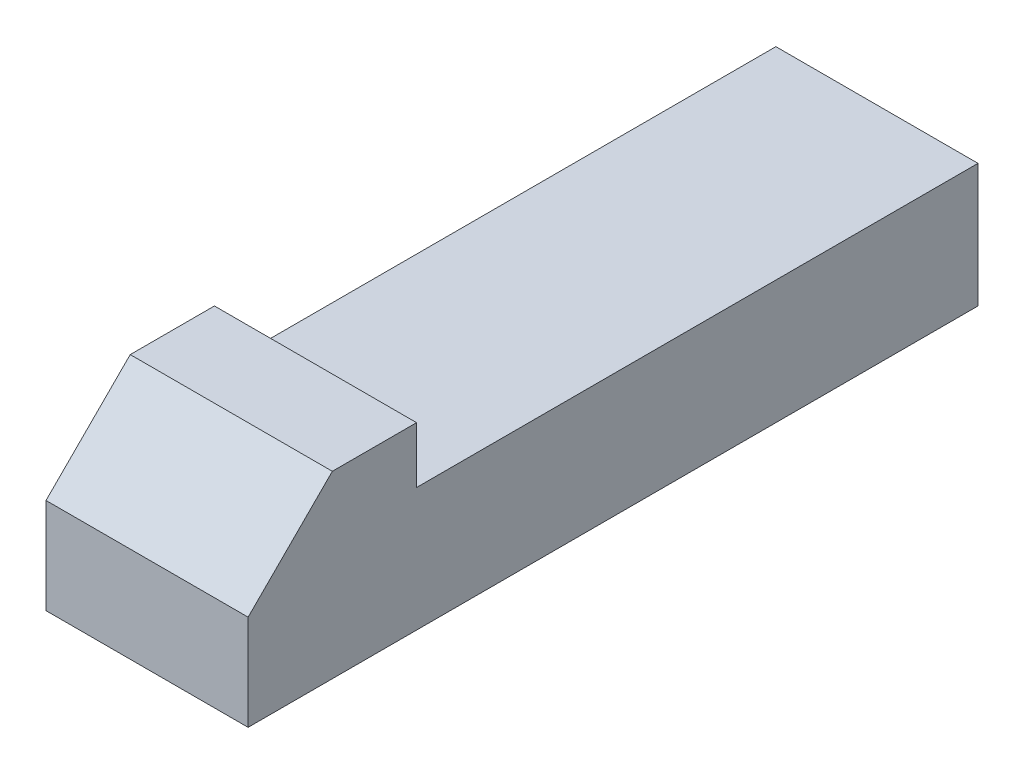
SolidWorks part; units mm, degrees
material "Cast Carbon Steel"
ref_plane "Front Plane" through (0, 0, 0) normal (0, 0, 1) x (1, 0, 0)
ref_plane "Top Plane" through (0, 0, 0) normal (0, 1, 0) x (1, 0, 0)
ref_plane "Right Plane" through (0, 0, 0) normal (1, 0, 0) x (0, 0, -1)
sketch "Sketch1" plane through (0, 0, 0) normal (0, 0, 1) x (1, 0, 0)
  line L1 (-9, -5.5) -> (9, -5.5)
  line L2 (-9, -5.5) -> (-9, 5.5)
  line L3 (-9, 5.5) -> (9, 5.5)
  line L4 (9, -5.5) -> (9, 5.5)
  line L5 (-9, -5.5) -> (9, 5.5) construction
  line L6 (-9, 5.5) -> (9, -5.5) construction
  point P0 (0, 0)
  dimension "D1" = 18
  dimension "D2" = 11
extrude "Boss-Extrude1" add sketch "Sketch1" against normal blind 65
sketch "Sketch2" plane through (0, 5.5, 0) normal (0, 1, 0) x (1, 0, 0)
  line L0 (9, 65) -> (9, 0) construction
  line L1 (-9, 0) -> (9, 0)
  line L2 (-9, 0) -> (-9, 15)
  line L3 (-9, 15) -> (9, 15)
  line L4 (9, 0) -> (9, 15)
  dimension "D1" = 15
extrude "Boss-Extrude2" add sketch "Sketch2" along normal blind 5
sketch "Sketch3" plane through (9, 0, 0) normal (1, 0, 0) x (0, 0, -1)
  line L0 (7.5, 10.5) -> (0, 3)
  line L1 (0, 10.5) -> (15, 10.5) construction
  line L2 (0, -5.5) -> (0, 10.5) construction
  line L3 (0, 3) -> (0, 10.5)
  line L4 (0, 10.5) -> (7.5, 10.5)
  dimension "D1" = 45
extrude "Cut-Extrude1" cut sketch "Sketch3" against normal through all
